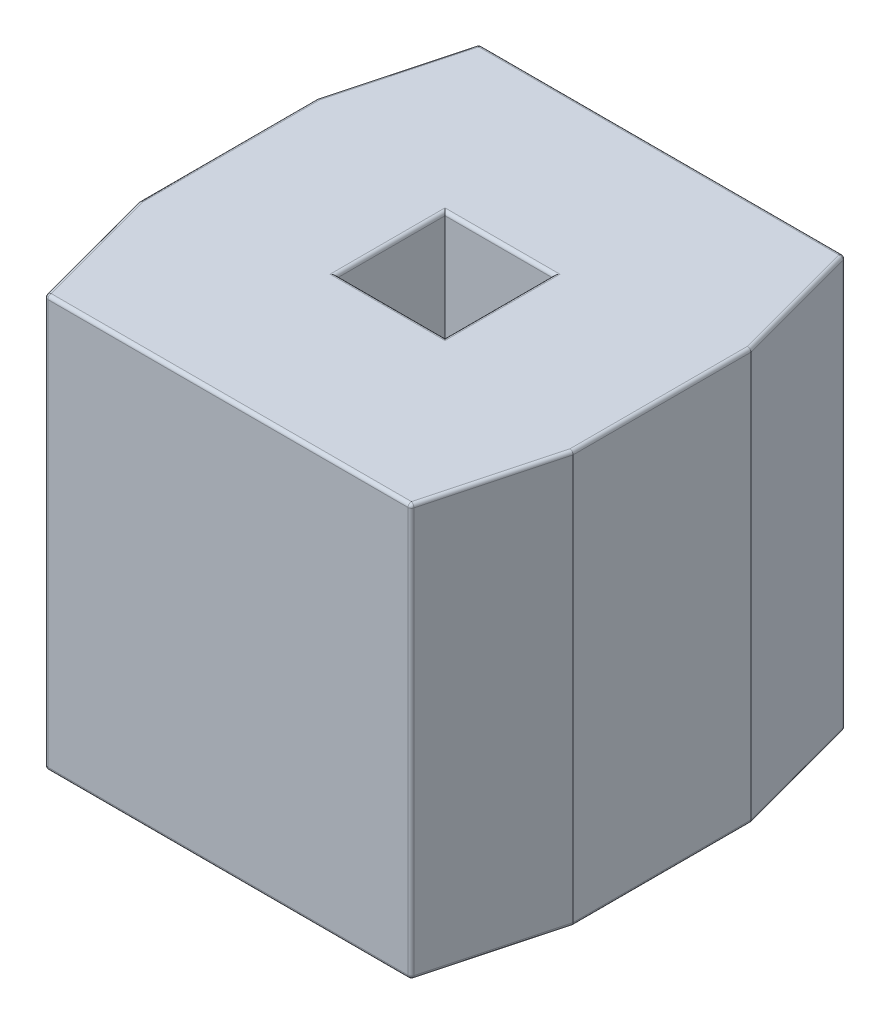
SolidWorks part; units mm, degrees
material "PVC 0.007 Plasticized"
ref_plane "Front Plane" through (0, 0, 0) normal (0, 0, 1) x (1, 0, 0)
ref_plane "Top Plane" through (0, 0, 0) normal (0, 1, 0) x (1, 0, 0)
ref_plane "Right Plane" through (0, 0, 0) normal (1, 0, 0) x (0, 0, -1)
sketch "Sketch1" plane through (0, 0, 0) normal (0, 1, 0) x (1, 0, 0)
  line L1 (-1.265, 1.265) -> (1.265, 1.265)
  line L2 (-1.265, 1.265) -> (-1.265, -1.265)
  line L3 (-1.265, -1.265) -> (1.265, -1.265)
  line L4 (1.265, 1.265) -> (1.265, -1.265)
  line L5 (-1.265, 1.265) -> (1.265, -1.265) construction
  line L6 (-1.265, -1.265) -> (1.265, 1.265) construction
  line L7 (-0.315, 0.315) -> (0.315, 0.315)
  line L8 (-0.315, 0.315) -> (-0.315, -0.315)
  line L9 (-0.315, -0.315) -> (0.315, -0.315)
  line L10 (0.315, 0.315) -> (0.315, -0.315)
  line L11 (-0.315, 0.315) -> (0.315, -0.315) construction
  line L12 (-0.315, -0.315) -> (0.315, 0.315) construction
  point P0 (0, 0)
  point P6 (0, 0)
  dimension "width spacer" = 2.53
  dimension "D2" = 0.63
extrude "Boss-Extrude1" add sketch "Sketch1" along normal blind 2.4
chamfer "Chamfer1" distance 0.2 angle 75 4 edges at (-1.265, 1.2, -1.265) (1.265, 1.2, -1.265) (-1.265, 1.2, 1.265) (1.265, 1.2, 1.265)
fillet "Fillet1" radius 0.02 28 edges at (1.065, 1.2, 1.265) (-1.065, 1.2, 1.265) (1.065, 1.2, -1.265) (-1.065, 1.2, -1.265) (0, 0, 0.315) (-0.315, 0, 0) (0, 0, -0.315) (0.315, 0, 0) (-1.165, 0, 0.8918) (0, 0, 1.265) (1.165, 0, 0.8918) (1.265, 0, 0) (1.165, 0, -0.8918) (0, 0, -1.265) (-1.165, 0, -0.8918) (-1.265, 0, 0) (-0.315, 2.4, 0) (0, 2.4, 0.315) (0.315, 2.4, 0) (0, 2.4, -0.315) (1.165, 2.4, -0.8918) (1.265, 2.4, 0) (1.165, 2.4, 0.8918) (0, 2.4, 1.265) (-1.165, 2.4, 0.8918) (-1.265, 2.4, 0) (-1.165, 2.4, -0.8918) (0, 2.4, -1.265)
equation "\"pin width\"= .63"
equation "\"spacer width\"= 2.53"
equation "\"spacer height\"= 2.4"
equation "\"width spacer@Sketch1\" = \"spacer width\""
equation "\"D1@Boss-Extrude1\"=\"spacer height\""
